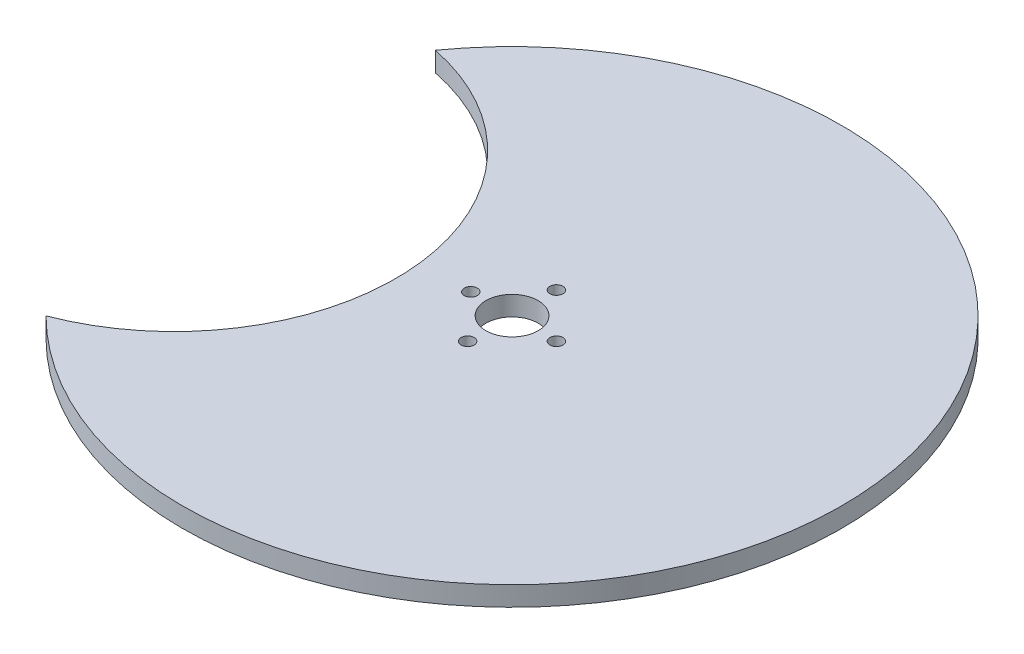
SolidWorks part; units mm, degrees
material "Oak"
ref_plane "Front Plane" through (0, 0, 0) normal (0, 0, 1) x (1, 0, 0)
ref_plane "Top Plane" through (0, 0, 0) normal (0, 1, 0) x (1, 0, 0)
ref_plane "Right Plane" through (0, 0, 0) normal (1, 0, 0) x (0, 0, -1)
sketch "Sketch1" plane through (0, 0, 0) normal (0, 1, 0) x (1, 0, 0)
  line L0 (0, 0) -> (-47.8342, -3.986) construction
  line L1 (0, 0) -> (-6.3185, 0) construction
  line L2 (0, 0) -> (6.8, 0) construction
  line L3 (0, 0) -> (0, 6.8) construction
  line L4 (0, 0) -> (0, -6.8) construction
  arc A0 (-35.6789, -35.7389) -> (-41.1019, 29.3408) centre (0, 0) ccw
  arc A1 (-35.6789, -35.7389) -> (-41.1019, 29.3408) centre (-47.8342, -3.986) ccw
  circle A2 centre (0, 0) radius 4
  circle A3 centre (-6.3185, 0) radius 1
  circle A4 centre (0, 6.8) radius 1
  circle A5 centre (6.8, 0) radius 1
  circle A6 centre (0, -6.8) radius 1
extrude "Boss-Extrude1" add sketch "Sketch1" along normal blind 3
